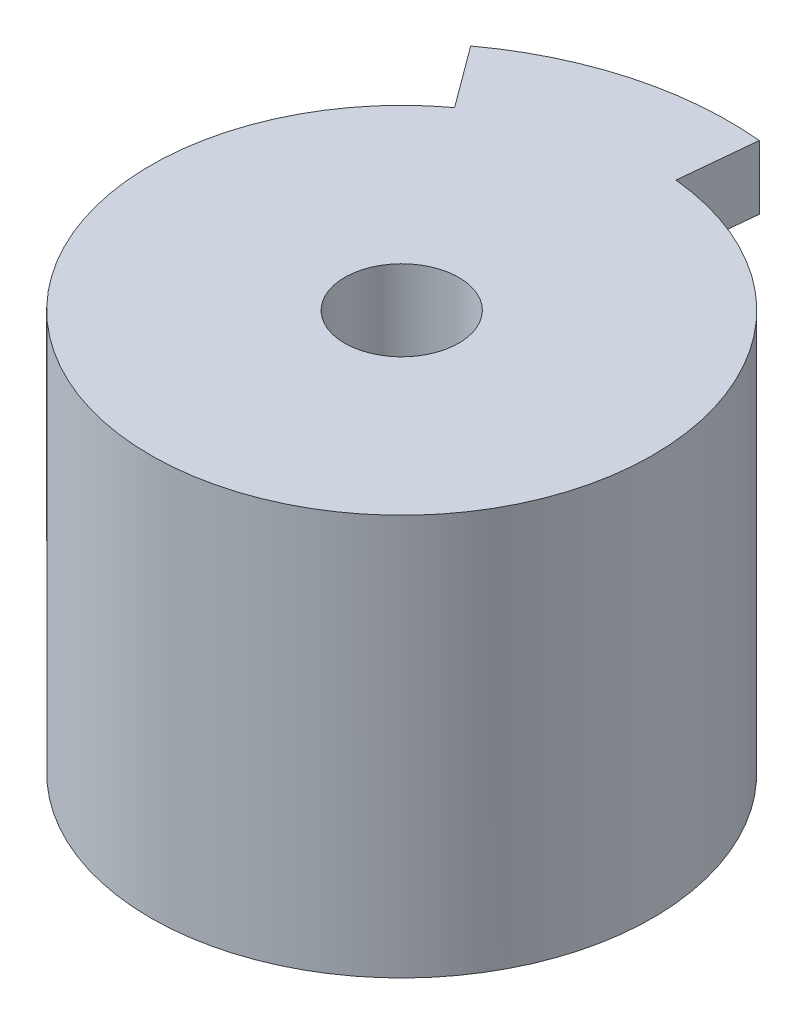
SolidWorks part; units mm, degrees
ref_plane "Front Plane" through (0, 0, 0) normal (0, 0, 1) x (1, 0, 0)
ref_plane "Top Plane" through (0, 0, 0) normal (0, 1, 0) x (1, 0, 0)
ref_plane "Right Plane" through (0, 0, 0) normal (1, 0, 0) x (0, 0, -1)
sketch "Sketch1" plane through (0, 0, 0) normal (0, 1, 0) x (1, 0, 0)
  circle A0 centre (0, 0) radius 12.655
extrude "Boss-Extrude1" add sketch "Sketch1" along normal blind 20.2
sketch "Sketch2" plane through (0, 20.2, 0) normal (0, 1, 0) x (1, 0, 0)
  line L0 (1.6009, 16.4222) -> (0, 0)
  line L1 (0, 0) -> (-9.7989, 13.2752)
  arc A1 (1.6009, 16.4222) -> (-9.7989, 13.2752) centre (0, 0) ccw
extrude "Boss-Extrude2" add sketch "Sketch2" against normal blind 3.22
sketch "Sketch3" plane through (0, 20.2, 0) normal (0, 1, 0) x (1, 0, 0)
  circle A0 centre (0, 0) radius 2.875
  dimension "D1" = 5.75
extrude "Cut-Extrude1" cut sketch "Sketch3" against normal blind 8.5
